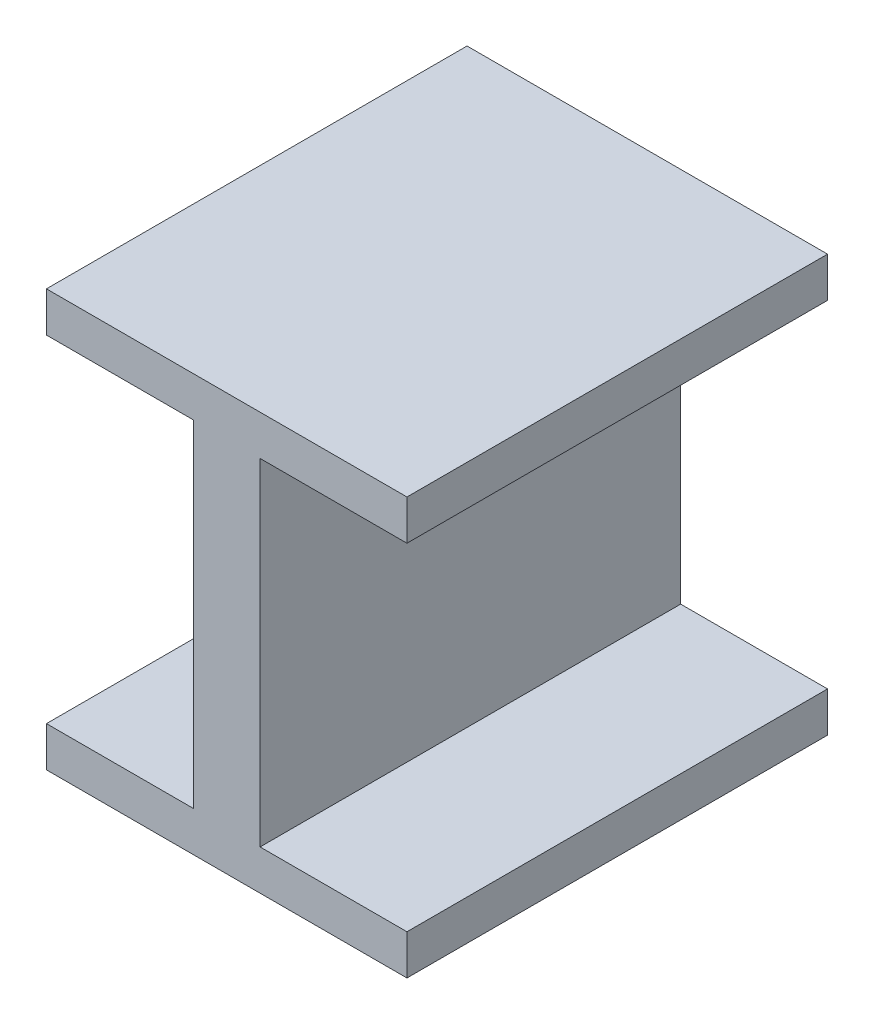
SolidWorks part; units mm, degrees
material "AISI 1010 钢，热轧条材"
ref_plane "前视基准面" through (0, 0, 0) normal (0, 0, 1) x (1, 0, 0)
ref_plane "上视基准面" through (0, 0, 0) normal (0, 1, 0) x (1, 0, 0)
ref_plane "右视基准面" through (0, 0, 0) normal (1, 0, 0) x (0, 0, -1)
sketch "草图1" plane through (0, 0, 0) normal (0, 1, 0) x (1, 0, 0)
  line L1 (-27, -31.5) -> (27, -31.5)
  line L2 (-27, -31.5) -> (-27, 31.5)
  line L3 (-27, 31.5) -> (27, 31.5)
  line L4 (27, -31.5) -> (27, 31.5)
  line L5 (-27, -31.5) -> (27, 31.5) construction
  line L6 (-27, 31.5) -> (27, -31.5) construction
  point P0 (0, 0)
  dimension "D1" = 63
  dimension "D2" = 54
extrude "凸台-拉伸1" add sketch "草图1" along normal blind 6
sketch "草图2" plane through (0, 6, 0) normal (0, 1, 0) x (1, 0, 0)
  line L0 (-27, -31.5) -> (27, -31.5) construction
  line L1 (5, 31.5) -> (-5, 31.5)
  line L2 (5, 31.5) -> (5, -31.5)
  line L3 (5, -31.5) -> (-5, -31.5)
  line L4 (-5, 31.5) -> (-5, -31.5)
  line L5 (5, 31.5) -> (-5, -31.5) construction
  line L6 (5, -31.5) -> (-5, 31.5) construction
  point P0 (0, 0)
  dimension "D1" = 10
extrude "凸台-拉伸2" add sketch "草图2" along normal blind 50.4
sketch "草图3" plane through (0, 56.4, 0) normal (0, 1, 0) x (1, 0, 0)
  line L1 (-27, 31.5) -> (27, 31.5)
  line L2 (-27, 31.5) -> (-27, -31.5)
  line L3 (-27, -31.5) -> (27, -31.5)
  line L4 (27, 31.5) -> (27, -31.5)
extrude "凸台-拉伸3" add sketch "草图3" along normal blind 6
